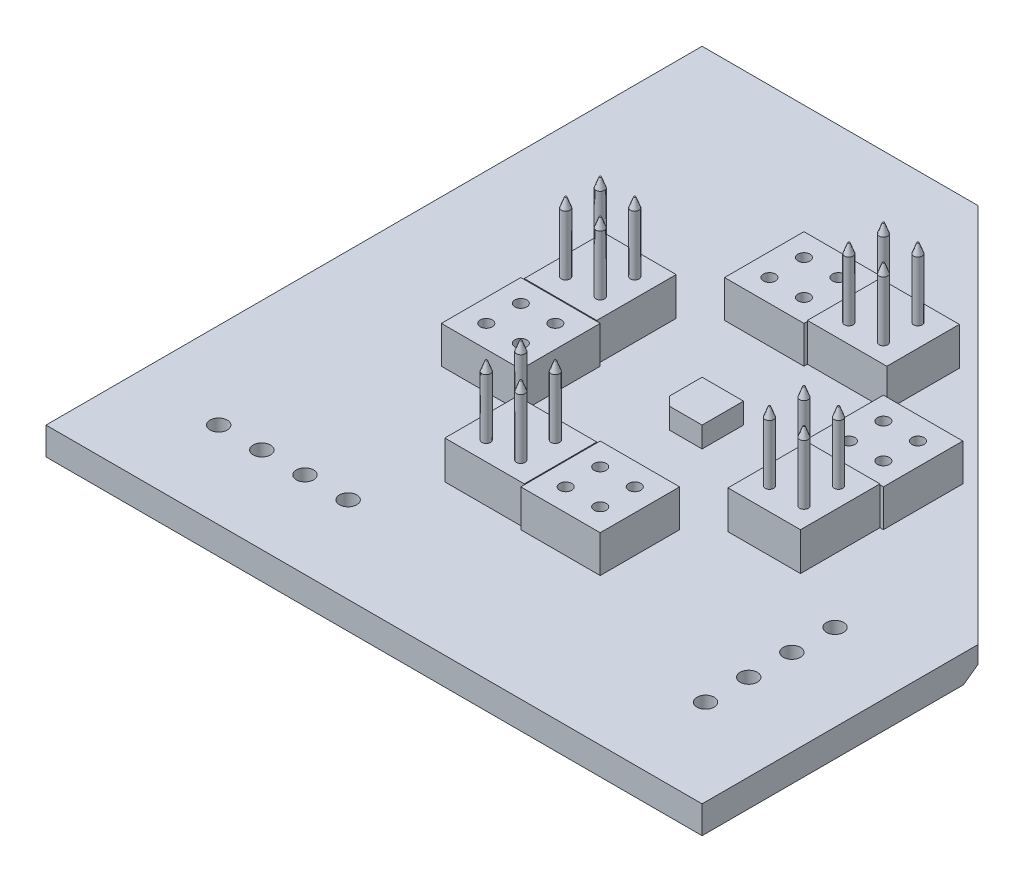
SolidWorks part; units mm, degrees
ref_plane "Front" through (0, 0, 0) normal (0, 0, 1) x (1, 0, 0)
ref_plane "Top" through (0, 0, 0) normal (0, 1, 0) x (1, 0, 0)
ref_plane "Right" through (0, 0, 0) normal (1, 0, 0) x (0, 0, -1)
sketch "Sketch1" plane through (0, 0, 0) normal (0, 1, 0) x (1, 0, 0)
  line L0 (19, -3.0194) -> (-3.0194, 19)
  line L1 (-19, 19) -> (-3.0194, 19)
  line L2 (-19, 19) -> (-19, -19)
  line L3 (-19, -19) -> (19, -19)
  line L4 (19, -3.0194) -> (19, -19)
  dimension "D1" = 19
  dimension "D2" = 19
  dimension "D3" = 19
  dimension "D4" = 19
  dimension "D5" = 45
  dimension "D6" = 11.3
extrude "Extrude1" add sketch "Sketch1" along normal blind 1.6
sketch "Sketch2" plane through (0, 1.6, 0) normal (0, 1, 0) x (-1, 0, 0)
  line L0 (-10.5, -4.6) -> (-10.5, 0)
  line L1 (4.6, -10.5) -> (0, -10.5)
  line L2 (4.6, -10.5) -> (4.6, -5.9)
  line L3 (4.6, -5.9) -> (0, -5.9)
  line L4 (0, -10.5) -> (0, -5.9)
  line L5 (-10.5, -4.6) -> (-5.9, -4.6)
  line L6 (-5.9, -4.6) -> (-5.9, 0)
  line L7 (-10.5, 0) -> (-5.9, 0)
  line L8 (-4.6, 10.5) -> (0, 10.5)
  line L9 (-4.6, 10.5) -> (-4.6, 5.9)
  line L10 (-4.6, 5.9) -> (0, 5.9)
  line L11 (0, 10.5) -> (0, 5.9)
  line L12 (10.5, 4.6) -> (10.5, 0)
  line L13 (10.5, 4.6) -> (5.9, 4.6)
  line L14 (5.9, 4.6) -> (5.9, 0)
  line L15 (10.5, 0) -> (5.9, 0)
  dimension "D1" = 4.6
  dimension "D2" = 4.6
  dimension "D3" = 5.9
  dimension "D4" = 5.9
extrude "Extrude2" add sketch "Sketch2" along normal blind 2.15
sketch "Sketch3" plane through (0, 1.6, 0) normal (0, 1, 0) x (-1, 0, 0)
  line L0 (0, -5.9) -> (0, -10.5) construction
  line L1 (-4.6, -10.3) -> (0, -10.3)
  line L2 (-4.6, -10.3) -> (-4.6, -6.1)
  line L3 (-4.6, -6.1) -> (0, -6.1)
  line L4 (0, -10.3) -> (0, -6.1)
  line L5 (-6.1, 4.6) -> (-6.1, 0)
  line L6 (-10.3, 0) -> (-6.1, 0)
  line L7 (-10.3, 4.6) -> (-6.1, 4.6)
  line L8 (-10.3, 4.6) -> (-10.3, 0)
  line L9 (4.6, 6.1) -> (0, 6.1)
  line L10 (0, 10.3) -> (0, 6.1)
  line L11 (4.6, 10.3) -> (4.6, 6.1)
  line L12 (4.6, 10.3) -> (0, 10.3)
  line L13 (6.1, -4.6) -> (6.1, 0)
  line L14 (10.3, 0) -> (6.1, 0)
  line L15 (10.3, -4.6) -> (6.1, -4.6)
  line L16 (10.3, -4.6) -> (10.3, 0)
  dimension "D1" = 4.6
  dimension "D2" = 4.2
  dimension "D3" = 6.1
  dimension "D4" = 6.1
extrude "Extrude3" add sketch "Sketch3" along normal blind 2.2
sketch "Sketch4" plane through (0, 3.75, 0) normal (0, 1, 0) x (-1, 0, 0)
  line L0 (2.3, -10.5) -> (2.3, -5.9) construction
  line L2 (4.6, -5.9) -> (0, -5.9) construction
  line L3 (4.6, -8.2) -> (0, -8.2) construction
  line L4 (0, -10.5) -> (4.6, -10.5) construction
  line L6 (4.6, -10.5) -> (4.6, -5.9) construction
  circle A0 centre (3.3, -9.2) radius 0.35
  circle A1 centre (1.3, -9.2) radius 0.35
  circle A2 centre (1.3, -7.2) radius 0.35
  circle A3 centre (3.3, -7.2) radius 0.35
  circle A4 centre (-9.2, -3.3) radius 0.35
  circle A5 centre (-9.2, -1.3) radius 0.35
  circle A6 centre (-7.2, -1.3) radius 0.35
  circle A7 centre (-7.2, -3.3) radius 0.35
  circle A8 centre (-3.3, 9.2) radius 0.35
  circle A9 centre (-1.3, 9.2) radius 0.35
  circle A10 centre (-1.3, 7.2) radius 0.35
  circle A11 centre (-3.3, 7.2) radius 0.35
  circle A12 centre (9.2, 3.3) radius 0.35
  circle A13 centre (9.2, 1.3) radius 0.35
  circle A14 centre (7.2, 1.3) radius 0.35
  circle A15 centre (7.2, 3.3) radius 0.35
  dimension "D3" = 0.7
  dimension "D1" = 1
  dimension "D2" = 1
extrude "Cut-Extrude1" cut sketch "Sketch4" against normal up to surface (2.15 mm away) up to face at (0, 1.6, 8.2)
sketch "Sketch5" plane through (0, 3.8, 0) normal (0, 1, 0) x (-1, 0, 0)
  line L0 (-2.3, -10.3) -> (-2.3, -6.1) construction
  line L1 (-4.6, -10.3) -> (0, -10.3) construction
  line L2 (0, -6.1) -> (-4.6, -6.1) construction
  line L3 (0, -8.2) -> (-4.6, -8.2) construction
  line L4 (0, -10.3) -> (0, -6.1) construction
  line L5 (-4.6, -6.1) -> (-4.6, -10.3) construction
  circle A0 centre (-1.3, -9.2) radius 0.25
  circle A1 centre (-3.3, -9.2) radius 0.25
  circle A2 centre (-3.3, -7.2) radius 0.25
  circle A3 centre (-1.3, -7.2) radius 0.25
  circle A4 centre (-7.2, 1.3) radius 0.25
  circle A5 centre (-9.2, 1.3) radius 0.25
  circle A6 centre (-9.2, 3.3) radius 0.25
  circle A7 centre (-7.2, 3.3) radius 0.25
  circle A8 centre (1.3, 7.2) radius 0.25
  circle A9 centre (1.3, 9.2) radius 0.25
  circle A10 centre (3.3, 9.2) radius 0.25
  circle A11 centre (3.3, 7.2) radius 0.25
  circle A12 centre (7.2, -1.3) radius 0.25
  circle A13 centre (9.2, -1.3) radius 0.25
  circle A14 centre (9.2, -3.3) radius 0.25
  circle A15 centre (7.2, -3.3) radius 0.25
  dimension "D3" = 0.5
  dimension "D1" = 1
  dimension "D2" = 1
extrude "Extrude4" add sketch "Sketch5" along normal blind 4
chamfer "Chamfer1" distance 0.2 angle 70 16 edges at (-1.3, 7.8, 9.45) (-3.3, 7.8, 8.95) (-3.3, 7.8, 7.45) (-1.3, 7.8, 6.95) (7.2, 7.8, 3.55) (9.2, 7.8, 3.05) (9.2, 7.8, 1.55) (7.2, 7.8, 1.05) (1.3, 7.8, -7.45) (3.3, 7.8, -6.95) (3.3, 7.8, -9.45) (1.3, 7.8, -8.95) (-9.2, 7.8, -1.05) (-7.2, 7.8, -3.05) (-9.2, 7.8, -3.55) (-7.2, 7.8, -1.55)
sketch "Sketch6" plane through (0, 0, 0) normal (0, -1, 0) x (1, 0, 0)
  line L0 (-19, -19) -> (-19, 19) construction
  line L1 (-13.5, -18.5) -> (-19.8, -18.5)
  line L2 (-19.8, -18.5) -> (-19.8, 12)
  line L3 (-19.8, 12) -> (-13.5, 12)
  line L4 (-13.5, 12) -> (-13.5, -18.5)
  dimension "D1" = 30.5
  dimension "D2" = 6.3
  dimension "D3" = 13.5
  dimension "D4" = 18.5
extrude "Extrude5" add sketch "Sketch6" along normal blind 2
sketch "Sketch7" plane through (0, 0, 0) normal (0, -1, 0) x (1, 0, 0)
  line L0 (-19, 19) -> (19, 19) construction
  line L1 (-8.75, 3.25) -> (-1.75, 3.25)
  line L2 (-8.75, 3.25) -> (-8.75, -3.75)
  line L3 (-8.75, -3.75) -> (-1.75, -3.75)
  line L4 (-1.75, 3.25) -> (-1.75, -3.75)
  line L5 (-19, 12) -> (-19, 19) construction
  dimension "D1" = 7
  dimension "D2" = 7
  dimension "D3" = 15.75
  dimension "D4" = 10.25
extrude "Extrude6" [suppressed] add sketch "Sketch7" along normal blind 1
chamfer "Chamfer2" distance 0.6 angle 45 1 edges at (7.9903, 0, -7.9903)
sketch "Sketch8" plane through (0, 1.6, 0) normal (0, 1, 0) x (-1, 0, 0)
  line L0 (1.2, 0.7) -> (0.7, 1.2)
  line L1 (1.2, -1.2) -> (-1.2, -1.2)
  line L2 (1.2, -1.2) -> (1.2, 0.7)
  line L3 (0.7, 1.2) -> (-1.2, 1.2)
  line L4 (-1.2, -1.2) -> (-1.2, 1.2)
  dimension "D1" = 1.2
  dimension "D2" = 1.2
  dimension "D3" = 1.2
  dimension "D4" = 1.2
  dimension "D5" = 0.5
  dimension "D6" = 0.5
extrude "Extrude7" add sketch "Sketch8" along normal blind 1.2
sketch "Sketch9" plane through (0, 0, 0) normal (0, -1, 0) x (1, 0, 0)
  line L0 (19, 19) -> (19, 3.8679) construction
  line L1 (9.5, 1.7) -> (7.5, 1.7)
  line L2 (9.5, 1.7) -> (9.5, -0.3)
  line L3 (9.5, -0.3) -> (7.5, -0.3)
  line L4 (7.5, 1.7) -> (7.5, -0.3)
  line L5 (-19, 19) -> (19, 19) construction
  line L6 (-19, 19) -> (19, 19) construction
  line L7 (-0.35, 6.15) -> (-2.35, 6.15)
  line L8 (-0.35, 6.15) -> (-0.35, 4.15)
  line L9 (-0.35, 4.15) -> (-2.35, 4.15)
  line L10 (-2.35, 6.15) -> (-2.35, 4.15)
  dimension "D1" = 9.5
  dimension "D2" = 17.3
  dimension "D3" = 2
  dimension "D4" = 2
  dimension "D5" = 19.35
  dimension "D6" = 12.85
  dimension "D7" = 2
  dimension "D8" = 2
extrude "Extrude8" [suppressed] add sketch "Sketch9" along normal blind 0.9
sketch "Sketch10" plane through (0, 0, 0) normal (0, -1, 0) x (1, 0, 0)
  line L0 (19, 19) -> (19, 3.8679) construction
  line L1 (1.35, 2.8) -> (0.6, 2.8)
  line L2 (1.55, 2.6) -> (1.55, -0.2)
  line L3 (1.35, -0.4) -> (0.6, -0.4)
  line L4 (0.4, 2.6) -> (0.4, -0.2)
  line L5 (-19, 19) -> (19, 19) construction
  arc A0 (0.4, -0.2) -> (0.6, -0.4) centre (0.6, -0.2) ccw
  arc A1 (0.6, 2.8) -> (0.4, 2.6) centre (0.6, 2.6) ccw
  arc A2 (1.55, 2.6) -> (1.35, 2.8) centre (1.35, 2.6) ccw
  arc A3 (1.35, -0.4) -> (1.55, -0.2) centre (1.35, -0.2) ccw
  point P10 (0.4, -0.4)
  point P15 (1.55, 2.8)
  point P18 (1.55, -0.4)
  dimension "D5" = 0.2
  dimension "D1" = 17.45
  dimension "D2" = 16.2
  dimension "D3" = 1.15
  dimension "D4" = 3.2
extrude "Extrude9" [suppressed] add sketch "Sketch10" along normal blind 1
sketch "Sketch11" plane through (0, 0, 0) normal (0, -1, 0) x (1, 0, 0)
  line L0 (19, 19) -> (19, 3.8679) construction
  line L1 (6, 8.3) -> (5.2, 8.3)
  line L2 (6, 8.3) -> (6, 6.7)
  line L3 (6, 6.7) -> (5.2, 6.7)
  line L4 (5.2, 8.3) -> (5.2, 6.7)
  line L5 (-19, 19) -> (19, 19) construction
  line L6 (-19, 12) -> (-19, 19) construction
  line L7 (-1.65, -0.85) -> (-2.45, -0.85)
  line L8 (-1.65, -0.85) -> (-1.65, 0.75)
  line L9 (-1.65, 0.75) -> (-2.45, 0.75)
  line L10 (-2.45, -0.85) -> (-2.45, 0.75)
  line L11 (-3.8679, -19) -> (-19, -19) construction
  line L12 (-19, -19) -> (-19, -18.5) construction
  line L13 (-7.25, -5.9) -> (-8.85, -5.9)
  line L14 (-7.25, -5.9) -> (-7.25, -5.1)
  line L15 (-7.25, -5.1) -> (-8.85, -5.1)
  line L16 (-8.85, -5.9) -> (-8.85, -5.1)
  line L17 (0.35, -0.85) -> (-0.45, -0.85)
  line L18 (0.35, -0.85) -> (0.35, 0.75)
  line L19 (0.35, 0.75) -> (-0.45, 0.75)
  line L20 (-0.45, -0.85) -> (-0.45, 0.75)
  line L21 (2.35, -0.85) -> (1.55, -0.85)
  line L22 (5.2, 2.55) -> (6, 2.55)
  line L23 (5.2, 2.55) -> (5.2, 4.15)
  line L24 (5.2, 4.15) -> (6, 4.15)
  line L25 (6, 2.55) -> (6, 4.15)
  line L26 (7.1, 2.55) -> (7.9, 2.55)
  line L27 (7.1, 2.55) -> (7.1, 4.15)
  line L28 (7.1, 4.15) -> (7.9, 4.15)
  line L29 (7.9, 2.55) -> (7.9, 4.15)
  line L30 (2.35, -0.85) -> (2.35, 0.75)
  line L31 (2.35, 0.75) -> (1.55, 0.75)
  line L32 (1.55, -0.85) -> (1.55, 0.75)
  line L33 (-7.25, -3.9) -> (-8.85, -3.9)
  line L34 (-7.25, -3.9) -> (-7.25, -3.1)
  line L35 (-7.25, -3.1) -> (-8.85, -3.1)
  line L36 (-8.85, -3.9) -> (-8.85, -3.1)
  line L37 (-7.25, -1.9) -> (-8.85, -1.9)
  line L38 (-7.25, -1.9) -> (-7.25, -1.1)
  line L39 (-7.25, -1.1) -> (-8.85, -1.1)
  line L40 (-8.85, -1.9) -> (-8.85, -1.1)
  line L42 (-7.4, -15.3) -> (-5.4, -15.3)
  line L43 (-7.4, -15.3) -> (-7.4, -14)
  line L44 (-7.4, -14) -> (-5.4, -14)
  line L45 (-5.4, -15.3) -> (-5.4, -14)
  point P20 (-19, -18.75)
  dimension "D1" = 13
  dimension "D2" = 10.7
  dimension "D3" = 0.8
  dimension "D4" = 1.6
  dimension "D5" = 16.55
  dimension "D6" = 18.15
  dimension "D7" = 1.6
  dimension "D8" = 0.8
  dimension "D9" = 10.15
  dimension "D10" = 13.1
  dimension "D11" = 0.8
  dimension "D12" = 1.6
  dimension "D13" = 4
  dimension "D14" = 4
  dimension "D15" = 3.7
  dimension "D16" = 11.6
  dimension "D17" = 4.15
  dimension "D18" = 1.6
  dimension "D19" = 1.9
  dimension "D20" = 0.8
  dimension "D21" = 1.3
  dimension "D22" = 2
extrude "Extrude10" add sketch "Sketch11" along normal blind 0.5
sketch "Sketch12" plane through (0, 0, 0) normal (0, -1, 0) x (1, 0, 0)
  line L1 (19, 19) -> (19, 3.8679) construction
  line L2 (-19, 19) -> (19, 19) construction
  line L15 (0, 0) -> (-18.2087, 0) construction
  line L23 (5.85, 12.05) -> (5.85, 10.15)
  line L24 (6.75, 10.15) -> (5.85, 10.15)
  line L25 (6.75, 12.05) -> (6.75, 10.15)
  line L26 (8.9, 12.05) -> (10.25, 12.05)
  line L27 (8, 12.05) -> (8, 10.15)
  line L28 (8.9, 10.15) -> (8, 10.15)
  line L29 (8.9, 12.05) -> (8.9, 10.15)
  line L30 (10.25, 12.05) -> (10.25, 10.15)
  line L31 (11.15, 10.15) -> (10.25, 10.15)
  line L32 (11.15, 12.05) -> (11.15, 10.15)
  line L33 (11.15, 12.05) -> (11.85, 12.05)
  line L34 (6.85, 15.75) -> (6.85, 17.65)
  line L35 (10.05, 17.65) -> (6.85, 17.65)
  line L36 (10.05, 15.75) -> (10.05, 17.65)
  line L37 (6.75, 12.05) -> (8, 12.05)
  line L38 (10.05, 15.75) -> (11.85, 15.75)
  line L39 (11.85, 15.75) -> (11.85, 12.05)
  line L40 (5.15, 12.05) -> (5.85, 12.05)
  line L41 (5.15, 15.75) -> (5.15, 12.05)
  line L42 (5.15, 15.75) -> (6.85, 15.75)
  point P4 (0, 0)
  dimension "D1" = 6.7
  dimension "D2" = 3.7
  dimension "D3" = 1.9
  dimension "D4" = 1.9
  dimension "D5" = 1.7
  dimension "D6" = 3.2
  dimension "D7" = 0.7
  dimension "D8" = 0.9
  dimension "D9" = 1.25
  dimension "D10" = 0.9
  dimension "D11" = 1.35
  dimension "D12" = 0.9
  dimension "D13" = 1.8
  dimension "D14" = 7.15
  dimension "D15" = 3.25
extrude "Extrude11" add sketch "Sketch12" along normal blind 0.3
sketch "Sketch13" plane through (0, -0.3, 0) normal (0, -1, 0) x (1, 0, 0)
  line L0 (5.15, 15.75) -> (5.15, 12.05) construction
  line L1 (11.84, 12.06) -> (5.16, 12.06)
  line L2 (11.84, 12.06) -> (11.84, 15.74)
  line L3 (11.84, 15.74) -> (5.16, 15.74)
  line L4 (5.16, 12.06) -> (5.16, 15.74)
  line L9 (6.85, 15.75) -> (5.15, 15.75) construction
  line L10 (5.15, 12.05) -> (5.85, 12.05) construction
  line L11 (11.85, 12.05) -> (11.85, 15.75) construction
  dimension "D1" = 0.01
  dimension "D2" = 0.01
  dimension "D3" = 0.01
  dimension "D4" = 0.01
extrude "Extrude12" add sketch "Sketch13" along normal blind 1.5
sketch "Sketch14" plane through (0, 0, 0) normal (0, -1, 0) x (1, 0, 0)
  line L0 (-19, 12) -> (-19, 19) construction
  line L1 (-19, 19) -> (19, 19) construction
  line L2 (-19, 19) -> (19, 19) construction
  line L3 (19, 19) -> (19, 3.8679) construction
  circle A0 centre (-14, 14) radius 0.5
  circle A1 centre (-11.5, 14) radius 0.5
  circle A2 centre (-9, 14) radius 0.5
  circle A3 centre (14, 11.3) radius 0.5
  circle A4 centre (-6.5, 14) radius 0.5
  circle A5 centre (14, 8.8) radius 0.5
  circle A6 centre (14, 13.8) radius 0.5
  circle A7 centre (14, 6.3) radius 0.5
  dimension "D1" = 1
  dimension "D5" = 5
  dimension "D7" = 5
  dimension "D8" = 1
  dimension "D2" = 5
  dimension "D3" = 5
  dimension "D4" = 7.5
  dimension "D6" = 5.2
  dimension "D9" = 7.5
  dimension "D10" = 5
extrude "Cut-Extrude2" cut sketch "Sketch14" against normal through all
sketch "Sketch15" plane through (0, 0, 0) normal (0, -1, 0) x (1, 0, 0)
  line L1 (-19, 19) -> (19, 19) construction
  line L2 (19, 19) -> (19, 3.8679) construction
  circle A0 centre (-14, 14) radius 0.5 construction
  circle A1 centre (-14, 14) radius 0.5
  circle A2 centre (-14, 14) radius 0.95
  circle A3 centre (-11.5, 14) radius 0.5
  circle A4 centre (-11.5, 14) radius 0.95
  circle A5 centre (-9, 14) radius 0.5
  circle A6 centre (-9, 14) radius 0.95
  circle A8 centre (-6.5, 14) radius 0.5
  circle A10 centre (-6.5, 14) radius 0.95
  circle A12 centre (14, 13.8) radius 0.5 construction
  circle A14 centre (14, 13.8) radius 0.5
  circle A16 centre (14, 13.8) radius 0.95
  circle A18 centre (14, 11.3) radius 0.5
  circle A20 centre (14, 11.3) radius 0.95
  circle A21 centre (14, 8.8) radius 0.5
  circle A22 centre (14, 8.8) radius 0.95
  circle A23 centre (14, 6.3) radius 0.5
  circle A24 centre (14, 6.3) radius 0.95
  dimension "D1" = 0.45
  dimension "D2" = 7.5
  dimension "D3" = 5
  dimension "D4" = 0.45
  dimension "D5" = 7.5
  dimension "D6" = 5
extrude "Extrude13" add sketch "Sketch15" along normal blind 0.05 and the other way blind 1.05
sketch "Sketch16" plane through (0, 0, 0) normal (0, -1, 0) x (1, 0, 0)
  line L1 (11.2, 8.35) -> (7.8, 8.35)
  line L2 (11.2, 8.35) -> (11.2, 6.65)
  line L3 (11.2, 6.65) -> (7.8, 6.65)
  line L4 (7.8, 8.35) -> (7.8, 6.65)
  line L6 (19, 19) -> (19, 3.8679) construction
  line L7 (-19, 19) -> (19, 19) construction
  dimension "D1" = 7.8
  dimension "D2" = 10.65
  dimension "D3" = 1.7
  dimension "D4" = 3.4
extrude "Extrude14" add sketch "Sketch16" along normal blind 1.6
sketch "Sketch17" plane through (0, 0, 0) normal (0, -1, 0) x (1, 0, 0)
  line L0 (-19, -19) -> (-19, -18.5) construction
  line L1 (-8.05, -5) -> (-9.25, -5)
  line L2 (-8.05, -5) -> (-8.05, -7.3)
  line L3 (-8.05, -7.3) -> (-9.25, -7.3)
  line L4 (-9.25, -5) -> (-9.25, -7.3)
  line L5 (-3.8679, -19) -> (-19, -19) construction
  point P4 (-19, -18.75)
  dimension "D1" = 9.75
  dimension "D2" = 11.7
  dimension "D3" = 1.2
  dimension "D4" = 2.3
extrude "Extrude15" [suppressed] add sketch "Sketch17" along normal blind 1.3
sketch "Sketch18" plane through (0, 0, 0) normal (0, -1, 0) x (1, 0, 0)
  line L0 (-19, -19) -> (-19, -18.5) construction
  line L1 (-10.55, -12.05) -> (-7.3, -12.05)
  line L2 (-10.55, -12.05) -> (-10.55, -8.8)
  line L3 (-10.55, -8.8) -> (-7.3, -8.8)
  line L4 (-7.3, -12.05) -> (-7.3, -8.8)
  line L5 (-3.8679, -19) -> (-19, -19) construction
  line L6 (-19, 19) -> (19, 19) construction
  line L7 (0.35, 4.4) -> (3.6, 4.4)
  line L8 (0.35, 4.4) -> (0.35, 7.65)
  line L9 (0.35, 7.65) -> (3.6, 7.65)
  line L10 (3.6, 4.4) -> (3.6, 7.65)
  line L11 (19, 19) -> (19, 3.8679) construction
  point P4 (-19, -18.75)
  dimension "D1" = 8.45
  dimension "D2" = 6.95
  dimension "D3" = 3.25
  dimension "D4" = 3.25
  dimension "D5" = 11.35
  dimension "D6" = 15.4
  dimension "D7" = 3.25
  dimension "D8" = 3.25
extrude "Extrude16" add sketch "Sketch18" along normal blind 1.1
sketch "Sketch19" plane through (0, 0, 0) normal (0, -1, 0) x (1, 0, 0)
  line L0 (-19, -19) -> (-19, -18.5) construction
  line L1 (-0.8, -8.45) -> (0.45, -8.45)
  line L2 (-0.8, -8.45) -> (-0.8, -7)
  line L3 (-0.8, -7) -> (-0.5, -7)
  line L4 (2.25, -8.45) -> (2.25, -7)
  line L5 (-3.8679, -19) -> (-19, -19) construction
  line L6 (1.95, -7) -> (2.25, -7)
  line L8 (0.95, -8.45) -> (0.95, -9.05)
  line L9 (0.95, -9.05) -> (0.45, -9.05)
  line L10 (0.45, -8.45) -> (0.45, -9.05)
  line L11 (0, -7) -> (1.45, -7)
  line L12 (1.95, -7) -> (1.95, -6.4)
  line L13 (1.95, -6.4) -> (1.45, -6.4)
  line L14 (1.45, -7) -> (1.45, -6.4)
  line L15 (0.95, -8.45) -> (2.25, -8.45)
  line L16 (0, -7) -> (0, -6.4)
  line L17 (0, -6.4) -> (-0.5, -6.4)
  line L18 (-0.5, -7) -> (-0.5, -6.4)
  dimension "D1" = 18.2
  dimension "D2" = 10.55
  dimension "D3" = 1.45
  dimension "D4" = 3.05
  dimension "D5" = 0.5
  dimension "D6" = 0.6
  dimension "D7" = 0.5
  dimension "D8" = 0.5
  dimension "D9" = 0.6
  dimension "D10" = 0.6
  dimension "D11" = 1.25
  dimension "D12" = 0.3
  dimension "D13" = 0.3
extrude "Extrude17" [suppressed] add sketch "Sketch19" along normal blind 0.3
sketch "Sketch20" [suppressed] plane through (0, -0.3, 0) normal (0, -1, 0) x (1, 0, 0)
  line L0 (-0.8, -7) -> (-0.8, -8.45) construction
  line L1 (-0.79, -7.01) -> (2.24, -7.01)
  line L2 (-0.79, -7.01) -> (-0.79, -8.44)
  line L3 (-0.79, -8.44) -> (2.24, -8.44)
  line L4 (2.24, -7.01) -> (2.24, -8.44)
  line L5 (-0.5, -7) -> (-0.8, -7) construction
  line L6 (-0.8, -8.45) -> (0.45, -8.45) construction
  line L7 (2.25, -8.45) -> (2.25, -7) construction
  dimension "D1" = 0.01
  dimension "D2" = 0.01
  dimension "D3" = 0.01
  dimension "D4" = 0.01
extrude "Extrude18" [suppressed] add sketch "Sketch20" along normal blind 0.8
